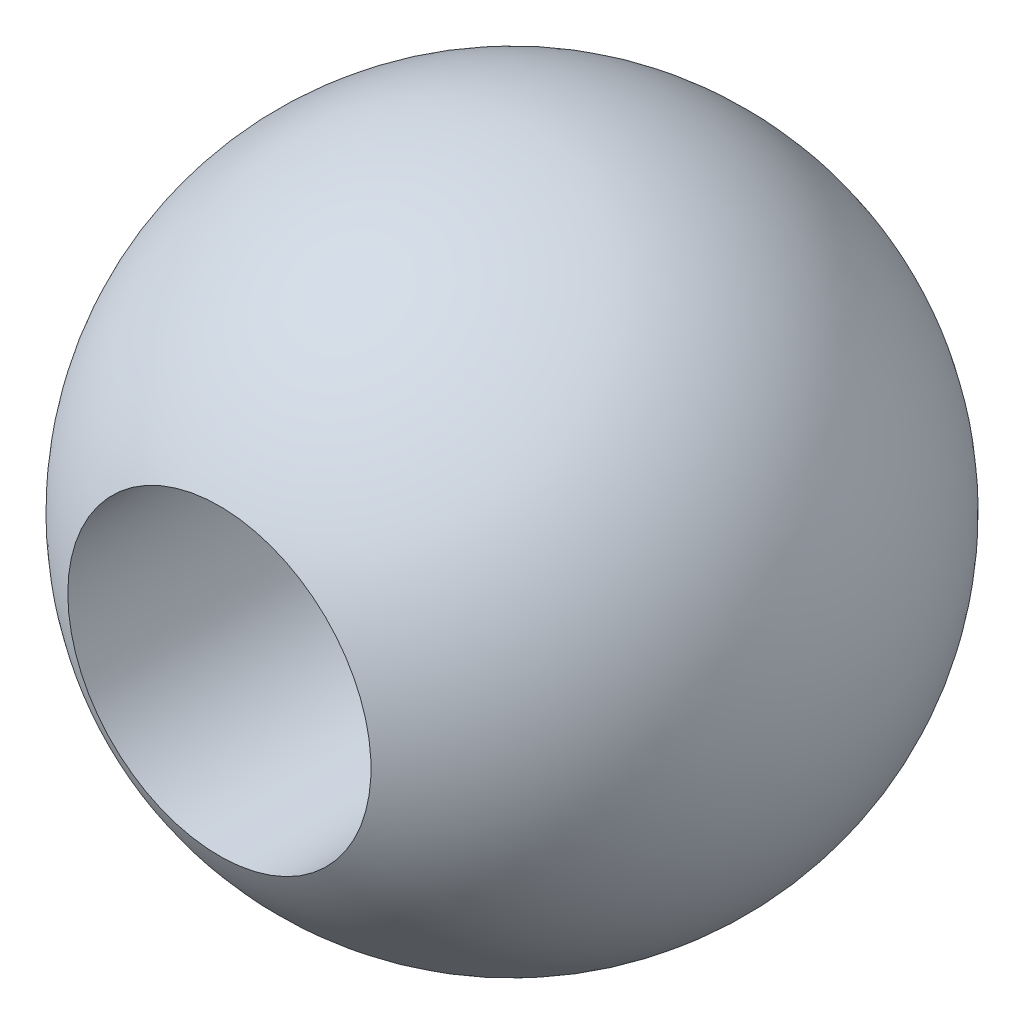
SolidWorks part; units mm, degrees
ref_plane "前视基准面" through (0, 0, 0) normal (0, 0, 1) x (1, 0, 0)
ref_plane "上视基准面" through (0, 0, 0) normal (0, 1, 0) x (1, 0, 0)
ref_plane "右视基准面" through (0, 0, 0) normal (1, 0, 0) x (0, 0, -1)
sketch "草图1" plane through (0, 0, 0) normal (0, 0, 1) x (1, 0, 0)
  line L0 (0, 2.5) -> (0, -2.5)
  arc A0 (0, 2.5) -> (0, -2.5) centre (0, 0) ccw
  dimension "D1" = 5
revolve "旋转1" add sketch "草图1" angle 360 about L0
sketch "草图3" plane through (0, 0, 0) normal (0, 0, 1) x (1, 0, 0)
  circle A0 centre (0, 0) radius 1.75
  dimension "D1" = 3.5
sketch "草图2" plane through (0, 0, 0) normal (0, 0, 1) x (1, 0, 0)
  circle A0 centre (0, 0) radius 1.15
  dimension "D1" = 2.3
extrude "切除-拉伸1" cut sketch "草图2" against normal mid plane 10
